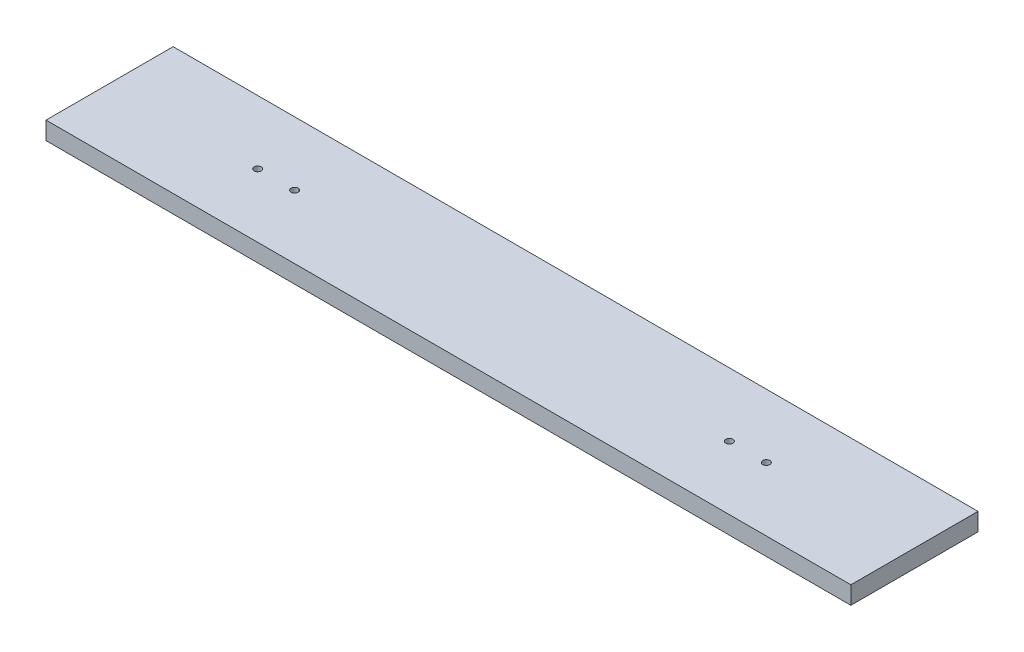
SolidWorks part; units mm, degrees
ref_plane "Front Plane" through (0, 0, 0) normal (0, 0, 1) x (1, 0, 0)
ref_plane "Top Plane" through (0, 0, 0) normal (0, 1, 0) x (1, 0, 0)
ref_plane "Right Plane" through (0, 0, 0) normal (1, 0, 0) x (0, 0, -1)
sketch "Sketch3" plane through (0, 0, 0) normal (0, 0, 1) x (1, 0, 0)
  line L1 (-401.955, 8.89) -> (401.955, 8.89)
  line L2 (-401.955, 8.89) -> (-401.955, -8.89)
  line L3 (-401.955, -8.89) -> (401.955, -8.89)
  line L4 (401.955, 8.89) -> (401.955, -8.89)
  line L5 (-401.955, 8.89) -> (401.955, -8.89) construction
  line L6 (-401.955, -8.89) -> (401.955, 8.89) construction
  point P0 (0, 0)
  dimension "D1" = 803.91
  dimension "D2" = 17.78
extrude "Boss-Extrude1" add sketch "Sketch3" along normal blind 127 contours L2 L1 L4 L3
sketch "Sketch4" plane through (0, 8.89, 0) normal (0, 1, 0) x (1, 0, 0)
  line L0 (-401.955, -63.5) -> (-254, -63.5) construction
  line L1 (-401.955, -127) -> (-401.955, 0) construction
  line L2 (401.955, -63.5) -> (254, -63.5) construction
  line L3 (401.955, -127) -> (401.955, 0) construction
  circle A0 centre (-254, -63.5) radius 3.556
  circle A1 centre (254, -63.5) radius 3.556
  dimension "D2" = 7.112
  dimension "D4" = 7.112
  dimension "D1" = 147.955
  dimension "D3" = 147.955
extrude "Cut-Extrude1" cut sketch "Sketch4" against normal through all
sketch "Sketch5" plane through (0, -8.89, 0) normal (0, -1, 0) x (1, 0, 0)
  line L0 (-254, 63.5) -> (-217.17, 63.5) construction
  line L1 (254, 63.5) -> (217.17, 63.5) construction
  circle A0 centre (-217.17, 63.5) radius 3.556
  circle A1 centre (217.17, 63.5) radius 3.556
  dimension "D2" = 7.112
  dimension "D4" = 7.112
  dimension "D1" = 36.83
  dimension "D3" = 36.83
extrude "Cut-Extrude2" cut sketch "Sketch5" against normal through all
